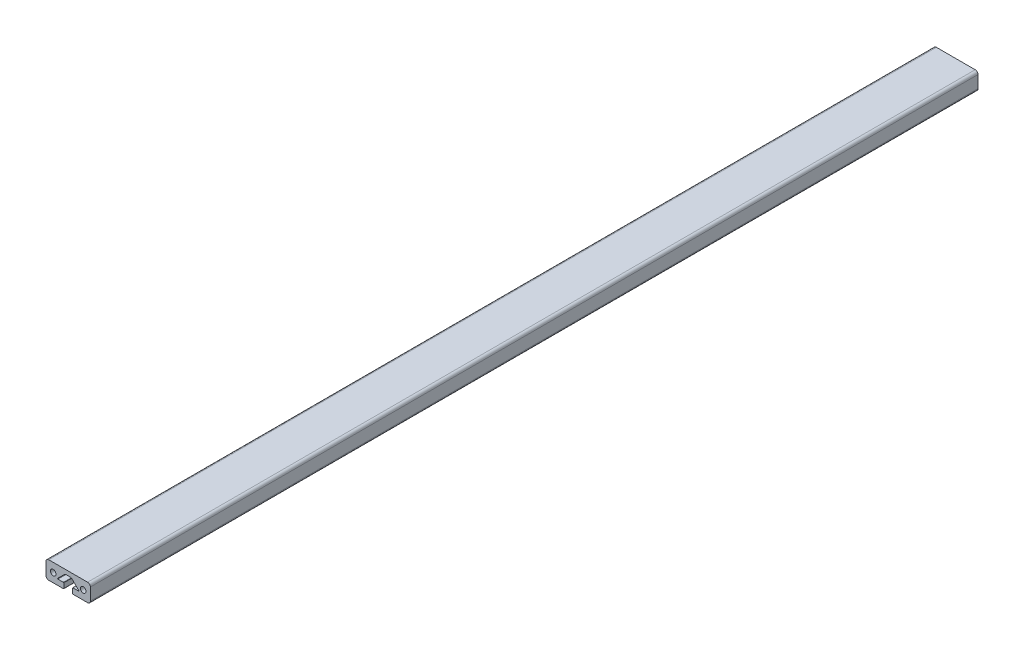
SolidWorks part; units mm, degrees
ref_plane "前视基准面" through (0, 0, 0) normal (0, 0, 1) x (1, 0, 0)
ref_plane "上视基准面" through (0, 0, 0) normal (0, 1, 0) x (1, 0, 0)
ref_plane "右视基准面" through (0, 0, 0) normal (1, 0, 0) x (0, 0, -1)
sketch "草图1" plane through (0, 0, 0) normal (0, 0, 1) x (1, 0, 0)
  line L0 (-1.0918, 3.7458) -> (2.8514, 3.7458)
  line L1 (4.2656, 3.16) -> (10.3677, -2.9421)
  line L2 (10.1556, -3.4542) -> (5.1798, -3.4542)
  line L3 (4.8798, -3.7542) -> (4.8798, -8.1542)
  line L4 (5.1798, -8.4542) -> (18.3798, -8.4542)
  line L5 (20.8798, -5.9542) -> (20.8798, 5.0458)
  line L6 (18.3798, 7.5458) -> (-16.6202, 7.5458)
  line L7 (-19.1202, 5.0458) -> (-19.1202, -5.9542)
  line L8 (-16.6202, -8.4542) -> (-3.4202, -8.4542)
  line L9 (-3.1202, -8.1542) -> (-3.1202, -3.7542)
  line L10 (-8.6081, -2.9421) -> (-2.506, 3.16)
  line L11 (-8.3959, -3.4542) -> (-3.4202, -3.4542)
  arc A0 (4.2656, 3.16) -> (2.8514, 3.7458) centre (2.8514, 1.7458) ccw
  arc A1 (10.1556, -3.4542) -> (10.3677, -2.9421) centre (10.1556, -3.1542) ccw
  arc A2 (5.1798, -3.4542) -> (4.8798, -3.7542) centre (5.1798, -3.7542) ccw
  arc A3 (4.8798, -8.1542) -> (5.1798, -8.4542) centre (5.1798, -8.1542) ccw
  arc A4 (18.3798, -8.4542) -> (20.8798, -5.9542) centre (18.3798, -5.9542) ccw
  arc A5 (20.8798, 5.0458) -> (18.3798, 7.5458) centre (18.3798, 5.0458) ccw
  arc A6 (-16.6202, 7.5458) -> (-19.1202, 5.0458) centre (-16.6202, 5.0458) ccw
  arc A7 (-19.1202, -5.9542) -> (-16.6202, -8.4542) centre (-16.6202, -5.9542) ccw
  arc A8 (-3.4202, -8.4542) -> (-3.1202, -8.1542) centre (-3.4202, -8.1542) ccw
  arc A9 (-1.0918, 3.7458) -> (-2.506, 3.16) centre (-1.0918, 1.7458) ccw
  arc A10 (-8.6081, -2.9421) -> (-8.3959, -3.4542) centre (-8.3959, -3.1542) ccw
  arc A11 (-3.1202, -3.7542) -> (-3.4202, -3.4542) centre (-3.4202, -3.7542) ccw
  circle A12 centre (-12.6202, -0.4542) radius 2.5
  circle A13 centre (14.3798, -0.4542) radius 2.5
extrude "凸台-拉伸1" add sketch "草图1" along normal blind 800
